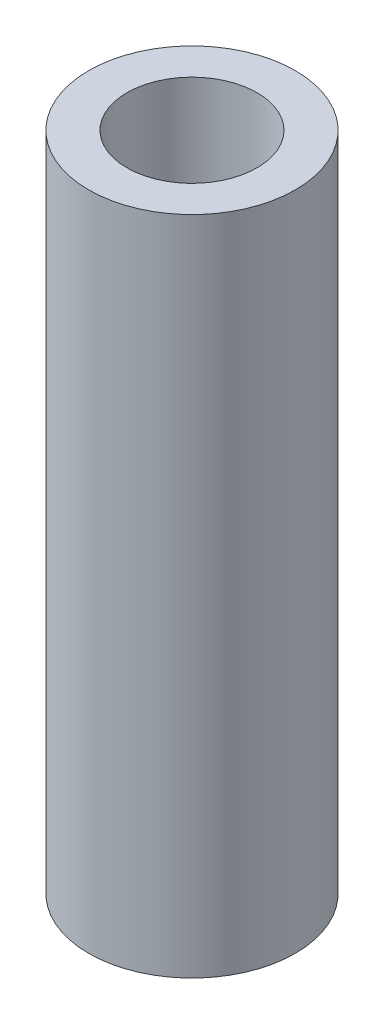
SolidWorks part; units mm, degrees
material "Custom Plastic"
ref_plane "X-Y Datum" through (0, 0, 0) normal (0, 0, 1) x (1, 0, 0)
ref_plane "X-Z Datum" through (0, 0, 0) normal (0, 1, 0) x (1, 0, 0)
ref_plane "Y-Z Datum" through (0, 0, 0) normal (1, 0, 0) x (0, 0, -1)
sketch "Sketch2" plane through (0, 0, 0) normal (0, 1, 0) x (1, 0, 0)
  circle A0 centre (0, 0) radius 3.175
  circle A1 centre (0, 0) radius 2
  dimension "D1" = 4
  dimension "D2" = 6.35
extrude "Boss-Extrude1" add sketch "Sketch2" against normal blind 20.32
